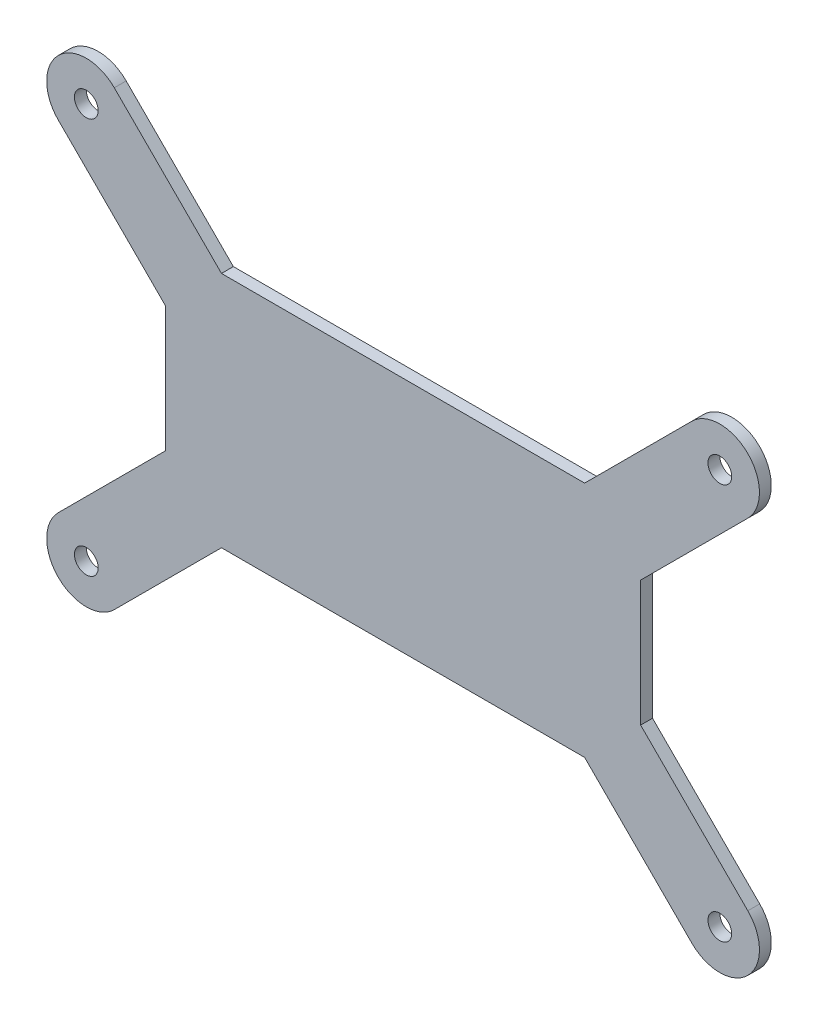
SolidWorks part; units mm, degrees
ref_plane "前视基准面" through (0, 0, 0) normal (0, 0, 1) x (1, 0, 0)
ref_plane "上视基准面" through (0, 0, 0) normal (0, 1, 0) x (1, 0, 0)
ref_plane "右视基准面" through (0, 0, 0) normal (1, 0, 0) x (0, 0, -1)
other "Configuration Table"
sketch "草图1" plane through (0, 0, 0) normal (0, 0, 1) x (1, 0, 0)
  line L0 (-40, 25) -> (-43.5355, 21.4645) construction
  line L1 (-45, 30) -> (45, 30) construction
  line L2 (-45, 30) -> (-45, -30) construction
  line L3 (-45, -30) -> (45, -30) construction
  line L4 (45, 30) -> (45, -30) construction
  line L5 (0, -30) -> (0, 30) construction
  line L6 (-45, 0) -> (45, 0) construction
  line L7 (-40, 25) -> (40, 25) construction
  line L8 (-40, 25) -> (-40, -25) construction
  line L9 (-40, -25) -> (40, -25) construction
  line L10 (40, 25) -> (40, -25) construction
  line L11 (0, -25) -> (0, 25) construction
  line L12 (-40, 0) -> (40, 0) construction
  line L13 (-30, 15) -> (30, 15) construction
  line L14 (-30, 15) -> (-30, -15) construction
  line L15 (-30, -15) -> (30, -15) construction
  line L16 (30, 15) -> (30, -15) construction
  line L17 (0, -15) -> (0, 15) construction
  line L18 (-30, 0) -> (30, 0) construction
  line L19 (-43.5355, 21.4645) -> (-30, 7.9289)
  line L20 (-36.4645, 28.5355) -> (-22.9289, 15)
  line L21 (-22.9289, 15) -> (-30, 7.9289) construction
  line L22 (-36.4645, -28.5355) -> (-22.9289, -15)
  line L23 (-43.5355, -21.4645) -> (-30, -7.9289)
  line L24 (43.5355, 21.4645) -> (30, 7.9289)
  line L25 (36.4645, 28.5355) -> (22.9289, 15)
  line L26 (36.4645, -28.5355) -> (22.9289, -15)
  line L27 (43.5355, -21.4645) -> (30, -7.9289)
  line L28 (-22.9289, 15) -> (22.9289, 15)
  line L29 (-30, 7.9289) -> (-30, -7.9289)
  line L30 (-22.9289, -15) -> (22.9289, -15)
  line L31 (30, 7.9289) -> (30, -7.9289)
  arc A0 (-36.4645, 28.5355) -> (-43.5355, 21.4645) centre (-40, 25) ccw
  arc A1 (-43.5355, -21.4645) -> (-36.4645, -28.5355) centre (-40, -25) ccw
  arc A2 (43.5355, 21.4645) -> (36.4645, 28.5355) centre (40, 25) ccw
  arc A3 (36.4645, -28.5355) -> (43.5355, -21.4645) centre (40, -25) ccw
  circle A4 centre (-40, 25) radius 1.5
  circle A5 centre (40, 25) radius 1.5
  circle A6 centre (40, -25) radius 1.5
  circle A7 centre (-40, -25) radius 1.5
  point P0 (0, 0)
  point P4 (0, 0)
  point P12 (0, 0)
  dimension "D8" = 3
  dimension "D9" = 3
  dimension "D10" = 3
  dimension "D11" = 3
  dimension "D1" = 90
  dimension "D2" = 60
  dimension "D3" = 50
  dimension "D4" = 80
  dimension "D5" = 60
  dimension "D6" = 10
  dimension "D7" = 45
extrude "凸台-拉伸1" add sketch "草图1" along normal blind 1.5
